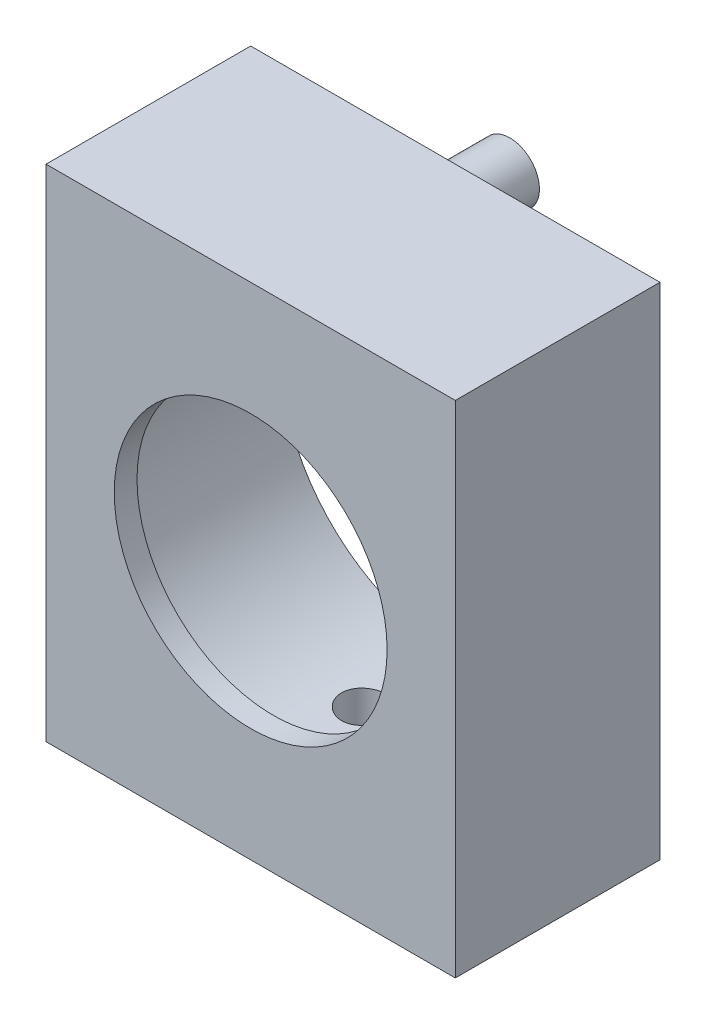
SolidWorks part; units mm, degrees
ref_plane "Plano frontal" through (0, 0, 0) normal (0, 0, 1) x (1, 0, 0)
ref_plane "Plano superior" through (0, 0, 0) normal (0, 1, 0) x (1, 0, 0)
ref_plane "Plano direito" through (0, 0, 0) normal (1, 0, 0) x (0, 0, -1)
sketch "Esboço6" plane through (0, 0, 0) normal (0, 0, 1) x (1, 0, 0)
  circle A0 centre (0, 0) radius 4.1
  circle A1 centre (0, 0) radius 5.25
  dimension "D1" = 10.5
  dimension "D2" = 8.2
extrude "Ressalto-extrusão3" add sketch "Esboço6" along normal blind 4 separate body
sketch "Esboço7" plane through (0, 0, 4) normal (0, 0, 1) x (1, 0, 0)
  circle A0 centre (0, 0) radius 5.25
  dimension "D1" = 10.5
extrude "Ressalto-extrusão4" add sketch "Esboço7" along normal blind 0.5
sketch "Esboço9" plane through (0, 0, 0) normal (0, 0, -1) x (-1, 0, 0)
  circle A5 centre (0, 4.75) radius 0.65
  circle A6 centre (0, -4.75) radius 0.65
  dimension "D1" = 9.5
  dimension "D3" = 4.75
extrude "Ressalto-extrusão5" add sketch "Esboço9" along normal blind 1.2
sketch "Esboço12" plane through (0, 0, 4) normal (0, 0, -1) x (-1, 0, 0)
  circle A1 centre (0, 0) radius 3
  dimension "D1" = 6
extrude "Corte-extrusão5" cut sketch "Esboço12" against normal blind 10
sketch "Esboço13" plane through (0, 0, 4) normal (0, 0, -1) x (-1, 0, 0)
  circle A0 centre (0, 0) radius 4.1
  circle A2 centre (0, 0) radius 3.85
  dimension "D1" = 7.7
extrude "Ressalto-extrusão6" add sketch "Esboço13" along normal up to surface (4 mm away) up to face at (-2.6408, 0, 0)
ref_plane "Plano2" through (0, -10, 0) normal (0, 1, 0) x (1, 0, 0)
sketch "Esboço15" plane through (0, 0, 0) normal (0, 0, -1) x (-1, 0, 0)
  line L1 (4.5, -5.5) -> (-4.5, -5.5)
  line L2 (4.5, -5.5) -> (4.5, 5.5)
  line L3 (4.5, 5.5) -> (-4.5, 5.5)
  line L4 (-4.5, -5.5) -> (-4.5, 5.5)
  line L5 (4.5, -5.5) -> (-4.5, 5.5) construction
  line L6 (4.5, 5.5) -> (-4.5, -5.5) construction
  circle A1 centre (0, 0) radius 3.85 construction
  circle A2 centre (0, 0) radius 3.85
  point P0 (0, 0)
  dimension "D1" = 11
  dimension "D2" = 9
sketch "Esboço16" plane through (0, 0, 0) normal (0, 0, -1) x (-1, 0, 0)
  line L0 (4.5, -5.5) -> (4.5, 5.5) construction
  line L1 (7.1653, -4.2946) -> (4.5, -4.2946)
  line L2 (7.1653, -4.2946) -> (7.1653, 3.6145)
  line L3 (7.1653, 3.6145) -> (4.5, 3.6145)
  line L4 (4.5, -4.2946) -> (4.5, 3.6145)
  line L5 (-4.5, -5.5) -> (-4.5, 5.5) construction
  line L6 (-4.5, -4.1382) -> (-6.5973, -4.1382)
  line L7 (-4.5, -4.1382) -> (-4.5, 3.257)
  line L8 (-4.5, 3.257) -> (-6.5973, 3.257)
  line L9 (-6.5973, -4.1382) -> (-6.5973, 3.257)
extrude "Corte-extrusão7" cut sketch "Esboço16" against normal blind 10
extrude "Ressalto-extrusão7" add sketch "Esboço15" against normal blind 4.5
sketch "Esboço14" plane through (0, -10, 0) normal (0, 1, 0) x (1, 0, 0)
  line L0 (-3, -4.5) -> (3, -4.5) construction
  circle A2 centre (0, -2) radius 0.5
  dimension "D1" = 2.5
extrude "Corte-extrusão6" cut sketch "Esboço14" along normal up to surface (6.15 mm away)
